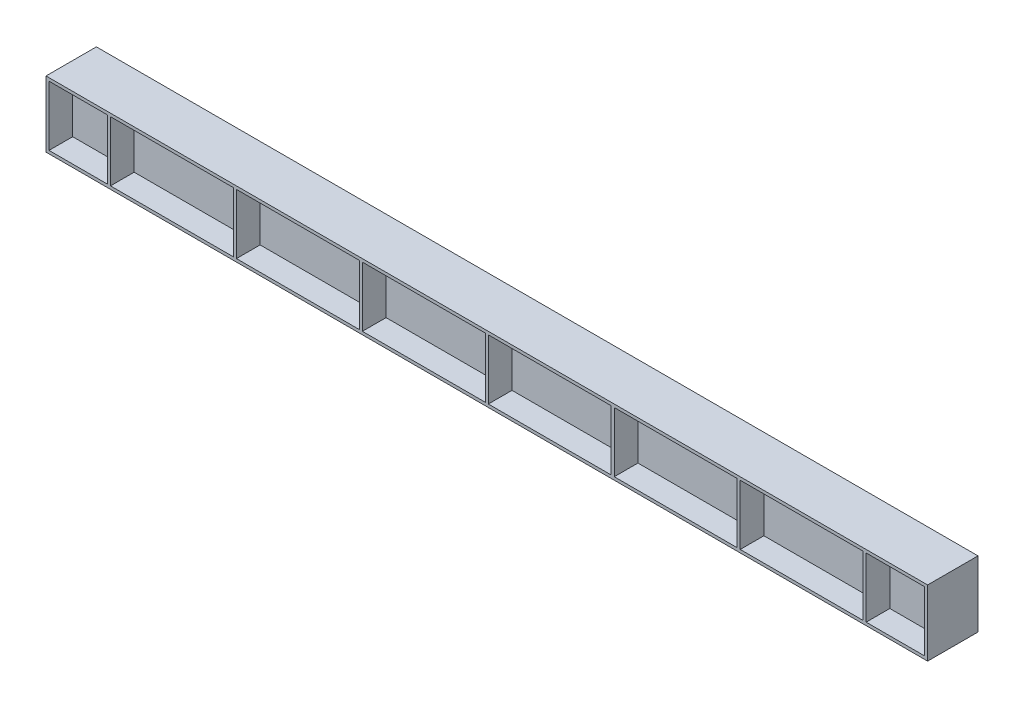
SolidWorks part; units mm, degrees
ref_plane "前视基准面" through (0, 0, 0) normal (0, 0, 1) x (1, 0, 0)
ref_plane "上视基准面" through (0, 0, 0) normal (0, 1, 0) x (1, 0, 0)
ref_plane "右视基准面" through (0, 0, 0) normal (1, 0, 0) x (0, 0, -1)
sketch "草图1" plane through (0, 0, 0) normal (0, 0, 1) x (1, 0, 0)
  line L1 (0, 0) -> (3500, 0)
  line L2 (0, 0) -> (0, 262)
  line L3 (0, 262) -> (3500, 262)
  line L4 (3500, 0) -> (3500, 262)
  dimension "D1" = 3500
  dimension "D2" = 262
extrude "拉伸1" add sketch "草图1" along normal blind 200
sketch "草图5" plane through (0, 0, 200) normal (0, 0, 1) x (1, 0, 0)
  line L0 (3500, 262) -> (0, 262) construction
  line L1 (12, 250) -> (244, 250)
  line L2 (12, 250) -> (12, 12)
  line L3 (12, 12) -> (244, 12)
  line L4 (244, 250) -> (244, 12)
  line L5 (0, 0) -> (3500, 0) construction
  line L6 (0, 262) -> (0, 0) construction
  line L8 (256, 250) -> (744, 250)
  line L9 (256, 250) -> (256, 12)
  line L10 (256, 12) -> (744, 12)
  line L11 (744, 250) -> (744, 12)
  line L12 (756, 250) -> (1244, 250)
  line L13 (756, 250) -> (756, 12)
  line L14 (756, 12) -> (1244, 12)
  line L15 (1244, 250) -> (1244, 12)
  line L16 (1256, 250) -> (1744, 250)
  line L17 (1256, 250) -> (1256, 12)
  line L18 (1256, 12) -> (1744, 12)
  line L19 (1744, 250) -> (1744, 12)
  line L20 (1756, 250) -> (2244, 250)
  line L21 (1756, 250) -> (1756, 12)
  line L22 (1756, 12) -> (2244, 12)
  line L23 (2244, 250) -> (2244, 12)
  line L24 (2256, 250) -> (2744, 250)
  line L25 (2256, 250) -> (2256, 12)
  line L26 (2256, 12) -> (2744, 12)
  line L27 (2744, 250) -> (2744, 12)
  line L28 (2756, 250) -> (3244, 250)
  line L29 (2756, 250) -> (2756, 12)
  line L30 (2756, 12) -> (3244, 12)
  line L31 (3244, 250) -> (3244, 12)
  line L32 (3256, 250) -> (3488, 250)
  line L33 (3256, 250) -> (3256, 12)
  line L34 (3256, 12) -> (3488, 12)
  line L35 (3488, 250) -> (3488, 12)
  dimension "D1" = 12
  dimension "D2" = 12
  dimension "D3" = 12
  dimension "D4" = 232
  dimension "D5" = 12
  dimension "D6" = 488
  dimension "D7" = 488
  dimension "D8" = 12
  dimension "D9" = 488
  dimension "D10" = 12
  dimension "D11" = 488
  dimension "D12" = 12
  dimension "D13" = 488
  dimension "D14" = 12
  dimension "D15" = 488
  dimension "D16" = 12
  dimension "D17" = 232
  dimension "D18" = 12
extrude "拉伸10" cut sketch "草图5" against normal through all
sketch "草图7" plane through (0, 0, 0) normal (0, -1, 0) x (1, 0, 0)
  line L0 (0, 100) -> (3607.9066, 100) construction
  line L1 (0, 200) -> (0, 0) construction
  line L2 (3500, 200) -> (3500, 0) construction
  line L3 (0, 106) -> (3500, 106)
  line L4 (0, 106) -> (0, 94)
  line L5 (0, 94) -> (3500, 94)
  line L6 (3500, 106) -> (3500, 94)
  dimension "D1" = 6
  dimension "D2" = 6
extrude "拉伸13" add sketch "草图7" against normal blind 260
